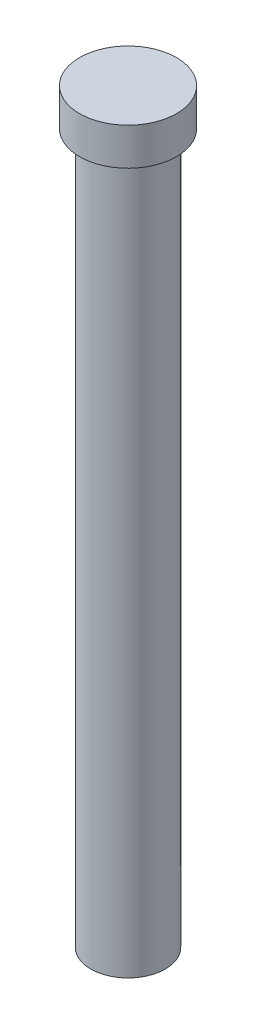
SolidWorks part; units mm, degrees
material "M2 HSS"
ref_plane "Front Plane" through (0, 0, 0) normal (0, 0, 1) x (1, 0, 0)
ref_plane "Top Plane" through (0, 0, 0) normal (0, 1, 0) x (1, 0, 0)
ref_plane "Right Plane" through (0, 0, 0) normal (1, 0, 0) x (0, 0, -1)
sketch "Sketch1" plane through (0, 0, 0) normal (0, 0, 1) x (1, 0, 0)
  line L0 (0, 0) -> (6.5, 0)
  line L2 (5, -5) -> (5, -100)
  line L3 (5, -100) -> (0, -100)
  line L4 (0, -100) -> (0, 0)
  line L5 (0, -105) -> (0, 5) construction
  line L6 (5, -5) -> (6.5, -5)
  line L7 (6.5, -5) -> (6.5, 0)
  dimension "D1" = 5
  dimension "D2" = 5
  dimension "D3" = 10
  dimension "D4" = 13
  dimension "D5" = 5
  dimension "D6" = 100
revolve "Revolve1" add sketch "Sketch1" angle 360 about L5
